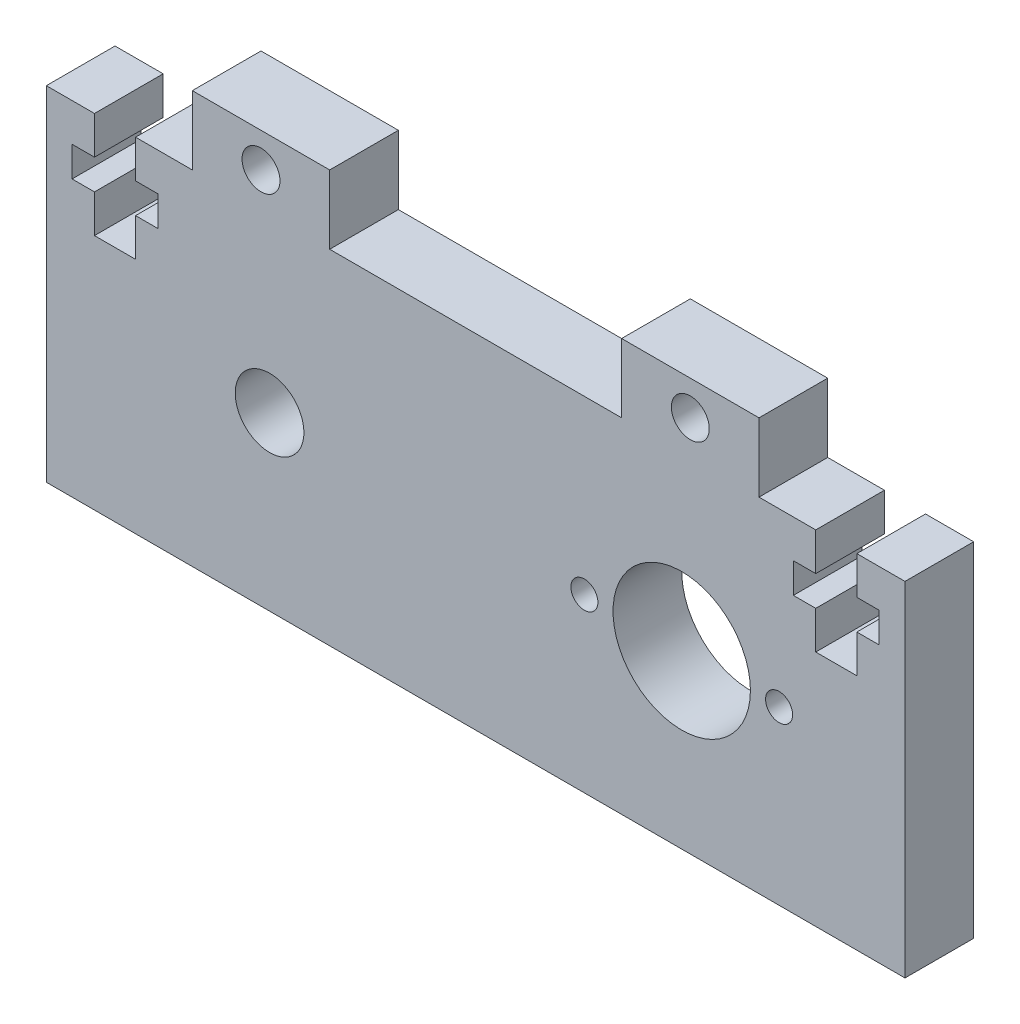
SolidWorks part; units mm, degrees
material "Beech"
ref_plane "Front Plane" through (0, 0, 0) normal (0, 0, 1) x (1, 0, 0)
ref_plane "Top Plane" through (0, 0, 0) normal (0, 1, 0) x (1, 0, 0)
ref_plane "Right Plane" through (0, 0, 0) normal (1, 0, 0) x (0, 0, -1)
sketch "Sketch1" plane through (0, 0, 0) normal (0, 0, 1) x (1, 0, 0)
  line L1 (-39.6875, -15.875) -> (0, -15.875)
  line L2 (-39.6875, -15.875) -> (-39.6875, 15.875)
  line L3 (-39.6875, 15.875) -> (0, 15.875)
  line L4 (0, -15.875) -> (0, 15.875)
  line L5 (-39.6875, -15.875) -> (0, 15.875) construction
  line L6 (-39.6875, 15.875) -> (0, -15.875) construction
  point P0 (-19.8438, 0)
  dimension "D1" = 31.75
  dimension "D2" = 39.6875
extrude "Boss-Extrude1" add sketch "Sketch1" along normal blind 6.35
sketch "Sketch2" plane through (0, 0, 6.35) normal (0, 0, 1) x (1, 0, 0)
  circle A0 centre (-19.05, 0) radius 3.175
  dimension "D1" = 6.35
  dimension "D2" = 19.05
extrude "Cut-Extrude1" cut sketch "Sketch2" against normal blind 6.35
sketch "Sketch3" plane through (0, 0, 6.35) normal (0, 0, 1) x (1, 0, 0)
  line L0 (-33.3375, 15.875) -> (-33.3375, 6.096) construction
  line L1 (0, 15.875) -> (-39.6875, 15.875) construction
  line L2 (-35.2362, 6.096) -> (-31.4389, 6.096)
  line L3 (-35.2362, 6.096) -> (-35.2362, 9.5964)
  line L4 (-35.2362, 9.5964) -> (-37.3062, 9.5964)
  line L5 (-37.3062, 9.5964) -> (-37.3062, 12.3746)
  line L6 (-37.3062, 12.3746) -> (-35.2362, 12.3746)
  line L7 (-35.2362, 12.3746) -> (-35.2362, 15.875)
  line L8 (-39.6875, 15.875) -> (-39.6875, -15.875) construction
  line L10 (-35.2362, 15.875) -> (-31.4388, 15.875)
  line L11 (-31.4388, 12.3746) -> (-31.4388, 15.875)
  line L12 (-29.3687, 12.3746) -> (-31.4388, 12.3746)
  line L13 (-29.3687, 9.5964) -> (-29.3687, 12.3746)
  line L14 (-31.4388, 9.5964) -> (-29.3687, 9.5964)
  line L15 (-31.4389, 6.096) -> (-31.4388, 9.5964)
  line L16 (-19.8437, 15.875) -> (-19.8438, -15.875) construction
  line L17 (-39.6875, -15.875) -> (0, -15.875) construction
  dimension "D1" = 3.7973
  dimension "D2" = 9.779
  dimension "D3" = 2.7781
  dimension "D4" = 3.9688
  dimension "D5" = 6.35
extrude "Cut-Extrude4" cut sketch "Sketch3" against normal blind 6.35
sketch "Sketch4" plane through (0, 0, 6.35) normal (0, 0, 1) x (1, 0, 0)
  line L1 (-26.1938, 22.225) -> (-13.4938, 22.225)
  line L2 (-26.1938, 22.225) -> (-26.1938, 15.875)
  line L3 (-26.1938, 15.875) -> (-13.4937, 15.875)
  line L4 (-13.4938, 22.225) -> (-13.4937, 15.875)
  line L5 (-26.1938, 22.225) -> (-13.4937, 15.875) construction
  line L6 (-26.1938, 15.875) -> (-13.4938, 22.225) construction
  line L7 (-19.8438, -15.875) -> (-19.8438, 15.875) construction
  line L8 (-39.6875, -15.875) -> (0, -15.875) construction
  line L9 (0, 15.875) -> (-31.4388, 15.875) construction
  circle A0 centre (-19.8438, 19.05) radius 1.7526
  point P0 (-19.8438, 19.05)
  point P5 (-19.8438, 15.875)
  dimension "D3" = 3.5052
  dimension "D1" = 6.35
  dimension "D2" = 12.7
extrude "Boss-Extrude2" add sketch "Sketch4" against normal blind 6.35
mirror "Mirror1" about plane through (0, -15.875, 6.35) normal (-1, 0, 0) of "Cut-Extrude4", "Boss-Extrude1", "Boss-Extrude2"
sketch "Sketch5" plane through (0, 0, 6.35) normal (0, 0, 1) x (1, 0, 0)
  line L0 (7.1438, 0) -> (30.9563, 0) construction
  circle A0 centre (19.05, 0) radius 6.35
  dimension "D1" = 12.7
  dimension "D2" = 19.05
  dimension "D3" = 23.8125
extrude "Cut-Extrude3" cut sketch "Sketch5" against normal blind 6.35
hole_wizard "Tap Drill for M3x0.5 Tap1" positions "Sketch6" profile "Sketch7" hole size "M3x0.5" standard "ANSI Metric" end condition through all
sketch "Sketch6" plane through (0, 0, 6.35) normal (0, 0, 1) x (1, 0, 0)
  line L0 (19.05, -6.35) -> (19.05, 6.35) construction
  circle A0 centre (19.05, 0) radius 6.35 construction
  point P0 (28.05, 0)
  point P2 (10.05, 0)
  dimension "D1" = 18
sketch "Sketch7" plane through (28.05, 0, 6.35) normal (1, 0, 0) x (0, -1, 0)
  line L0 (0, 0) -> (0, 6.35)
  line L1 (0, 6.35) -> (1.25, 6.35)
  line L2 (1.25, 6.35) -> (1.25, 0)
  line L5 (1.25, 0) -> (0, 0)
  line L11 (0, -6.35) -> (0, 107.95) construction
  dimension "Thru Hole Dia." = 2.5
  dimension "Thru Hole Depth" = 6.35
